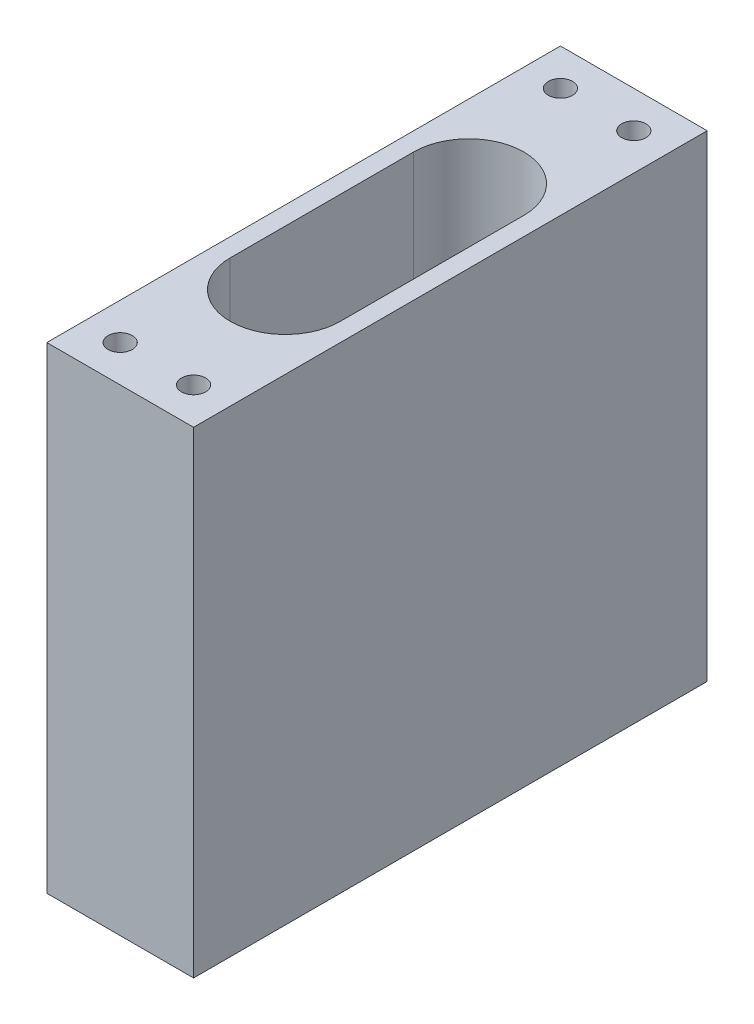
SolidWorks part; units mm, degrees
material "7079 Alloy"
ref_plane "Front Plane" through (0, 0, 0) normal (0, 0, 1) x (1, 0, 0)
ref_plane "Top Plane" through (0, 0, 0) normal (0, 1, 0) x (1, 0, 0)
ref_plane "Right Plane" through (0, 0, 0) normal (1, 0, 0) x (0, 0, -1)
sketch "Sketch1" plane through (0, 0, 0) normal (0, 1, 0) x (1, 0, 0)
  line L1 (10, -35) -> (-10, -35)
  line L2 (10, -35) -> (10, 35)
  line L3 (10, 35) -> (-10, 35)
  line L4 (-10, -35) -> (-10, 35)
  line L5 (10, -35) -> (-10, 35) construction
  line L6 (10, 35) -> (-10, -35) construction
  point P0 (0, 0)
  dimension "D1" = 20
  dimension "D2" = 70
extrude "Boss-Extrude1" add sketch "Sketch1" along normal mid plane 65
sketch "Sketch2" plane through (0, -32.5, 0) normal (0, -1, 0) x (1, 0, 0)
  line L0 (0, -12.5) -> (0, 12.5) construction
  line L2 (-7.5, -12.5) -> (-7.5, 12.5)
  line L3 (7.5, -12.5) -> (7.5, 12.5)
  arc A0 (-7.5, -12.5) -> (7.5, -12.5) centre (0, -12.5) ccw
  arc A1 (7.5, 12.5) -> (-7.5, 12.5) centre (0, 12.5) ccw
  point P2 (0, 0)
  dimension "D2" = 7.5
  dimension "D1" = 25
extrude "Cut-Extrude1" cut sketch "Sketch2" against normal through all
sketch "Sketch3" plane through (0, -32.5, 0) normal (0, -1, 0) x (1, 0, 0)
  line L0 (0, 0) -> (0, 35) construction
  line L1 (-10, 35) -> (10, 35) construction
  line L2 (0, 0) -> (10, 0) construction
  line L3 (10, 35) -> (10, -35) construction
  circle A0 centre (5, 30) radius 1.5
  circle A1 centre (-5, 30) radius 1.5
  circle A2 centre (5, -30) radius 1.5
  circle A3 centre (-5, -30) radius 1.5
  dimension "D2" = 60
  dimension "D3" = 3
  dimension "D1" = 10
extrude "Cut-Extrude2" cut sketch "Sketch3" against normal blind 100
hole_wizard "M4 Tapped Hole1" positions "3DSketch1" profile "Sketch4" tap size "M4" standard "DIN"
sketch3d "3DSketch1"
  line L0 (-5, 32.5, 30) -> (-5, -32.5, 30) construction
  line L1 (5, 32.5, 30) -> (5, -32.5, 30) construction
  line L2 (5, 32.5, -30) -> (5, -32.5, -30) construction
  line L3 (-5, 32.5, -30) -> (-5, -32.5, -30) construction
  point P0 (-5, 32.5, 30)
  point P4 (5, 32.5, 30)
  point P8 (5, 32.5, -30)
  point P12 (-5, 32.5, -30)
sketch "Sketch4" plane through (-5, 32.5, 30) normal (1, 0, 0) x (0, 0, 1)
  line L0 (0, 0) -> (0, 103.0914)
  line L1 (0, 103.0914) -> (1.65, 102.1)
  line L2 (1.65, 102.1) -> (1.65, 0)
  line L5 (1.65, 0) -> (0, 0)
  line L10 (0, 103.0914) -> (-1.65, 102.1) construction
  line L11 (0, -6.35) -> (0, 107.95) construction
  dimension "Tap Drill Dia." = 3.3
  dimension "Tap Drill Depth" = 102.1
  dimension "Drill Angle" = 118
cosmetic thread "Hole Thread1" parameters "D1"=65, "D2"=4
cosmetic thread "Hole Thread2" parameters "D1"=65, "D2"=4
cosmetic thread "Hole Thread3" parameters "D1"=65, "D2"=4
cosmetic thread "Hole Thread4" parameters "D1"=65, "D2"=4
